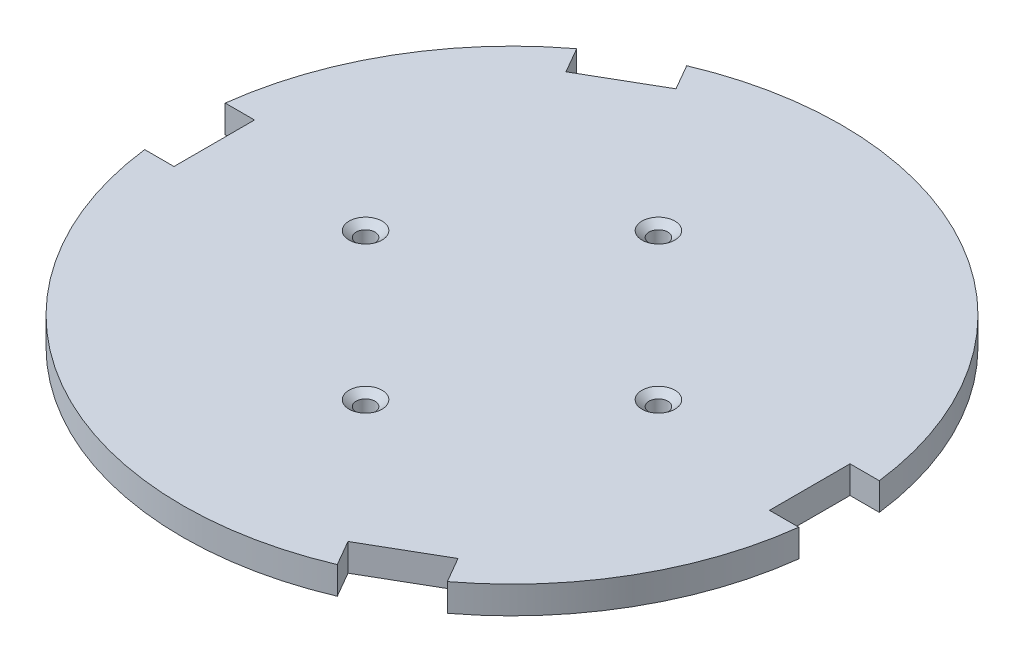
SolidWorks part; units mm, degrees
material "6061-T6 (SS)"
ref_plane "Front Plane" through (0, 0, 0) normal (0, 0, 1) x (1, 0, 0)
ref_plane "Top Plane" through (0, 0, 0) normal (0, 1, 0) x (1, 0, 0)
ref_plane "Right Plane" through (0, 0, 0) normal (1, 0, 0) x (0, 0, -1)
sketch "Sketch1" plane through (0, 0, 0) normal (0, 1, 0) x (1, 0, 0)
  circle A0 centre (0, 0) radius 57.15
  dimension "D1" = 114.3
extrude "Boss-Extrude1" add sketch "Sketch1" along normal blind 4.7625 contours A0
sketch "Sketch2" plane through (0, 4.7625, 0) normal (0, 1, 0) x (1, 0, 0)
  line L0 (0, 0) -> (57.15, 0) construction
  line L1 (0, 0) -> (0, -60.8636) construction
  line L2 (51.6415, 6.985) -> (51.6415, -6.985)
  line L3 (51.6415, -6.985) -> (56.7215, -6.985)
  line L4 (51.6415, 6.985) -> (56.7215, 6.985)
  line L5 (-51.6415, 6.985) -> (-56.7215, 6.985)
  line L6 (-51.6415, -6.985) -> (-56.7215, -6.985)
  line L7 (-51.6415, 6.985) -> (-51.6415, -6.985)
  arc A0 (56.7215, 6.985) -> (56.7215, -6.985) centre (0, 0) cw
  circle A1 centre (0, 0) radius 57.15 construction
  arc A2 (-56.7215, 6.985) -> (-56.7215, -6.985) centre (0, 0) ccw
  dimension "D1" = 13.97
  dimension "D2" = 5.08
extrude "Cut-Extrude2" cut sketch "Sketch2" against normal up to next
sketch "Sketch3" plane through (0, 4.7625, 0) normal (0, 1, 0) x (1, 0, 0)
  line L0 (0, 0) -> (59.9131, 0) construction
  line L1 (0, 0) -> (30.2146, -52.3333) construction
  line L2 (19.7716, -48.2154) -> (31.87, -41.2304)
  line L3 (31.87, -41.2304) -> (34.41, -45.6298)
  line L4 (19.7716, -48.2154) -> (22.3116, -52.6148)
  line L5 (0, 0) -> (49.4934, 28.575) construction
  line L6 (-31.87, 41.2304) -> (-34.41, 45.6298)
  line L7 (-19.7716, 48.2154) -> (-22.3116, 52.6148)
  line L8 (-31.87, 41.2304) -> (-19.7716, 48.2154)
  arc A0 (-56.7215, -6.985) -> (56.7215, -6.985) centre (0, 0) ccw construction
  arc A1 (22.3116, -52.6148) -> (34.41, -45.6298) centre (0, 0) ccw
  arc A3 (-34.41, 45.6298) -> (-22.3116, 52.6148) centre (0, 0) cw
  point P13 (25.8208, -44.7229)
  dimension "D1" = 60
  dimension "D2" = 13.97
  dimension "D3" = 5.08
extrude "Cut-Extrude3" cut sketch "Sketch3" against normal up to next
sketch "Sketch4" plane through (0, 4.7625, 0) normal (0, 1, 0) x (1, 0, 0)
  line L0 (25.4, 0) -> (0, 0)
  line L1 (0, 25.4) -> (0, 0)
  line L2 (-23.876, 0) -> (-25.4, 0)
  line L3 (0, -23.876) -> (0, -25.4)
  line L4 (0, 0) -> (0, -25.4)
  line L5 (0, 0) -> (-25.4, 0)
  line L6 (0, 0) -> (0, 25.4)
  circle A0 centre (0, 0) radius 38.1
  circle A1 centre (0, 0) radius 25.4
  circle A2 centre (0, 0) radius 9.1384
  circle A3 centre (25.4, 0) radius 1.524
  circle A4 centre (0, -25.4) radius 1.524
  circle A5 centre (0, 25.4) radius 1.524
  circle A6 centre (-25.4, 0) radius 1.524
  point P2 (0, 0)
  point P16 (0, 0)
  point P17 (0, 0)
  point P19 (0, 0)
  point P20 (0, 0)
  point P21 (0, 0)
  point P22 (0, 0)
  dimension "D1" = 76.2
  dimension "D2" = 50.8
  dimension "D3" = 90
  dimension "D4" = 3.048
hole_wizard "CSK for #4 Flat Head Machine Screw (100)1" positions "Sketch5" profile "Sketch6" countersink size "#4" standard "ANSI Inch" end condition up to next
sketch "Sketch5" plane through (0, 4.7625, 0) normal (0, 1, 0) x (1, 0, 0)
  point P0 (25.4, 0)
  point P3 (0, -25.4)
  point P6 (0, 25.4)
  point P9 (-25.4, 0)
sketch "Sketch6" plane through (25.4, 4.7625, 0) normal (1, 0, 0) x (0, 0, 1)
  line L0 (0, 0) -> (0, 4.7625)
  line L1 (0, 4.7625) -> (1.6319, 4.7625)
  line L2 (1.6319, 4.7625) -> (1.632, 1.0284)
  line L3 (1.632, 1.0284) -> (2.8575, 0)
  line L5 (2.8575, 0) -> (0, 0)
  line L6 (-1.632, 1.0284) -> (-2.8575, 0) construction
  line L11 (0, -6.35) -> (0, 107.95) construction
  dimension "Thru Hole Dia." = 3.2639
  dimension "Thru Hole Depth" = 4.7625
  dimension "Near C'Sink Dia." = 5.715
  dimension "Near C'Sink Angle" = 100
